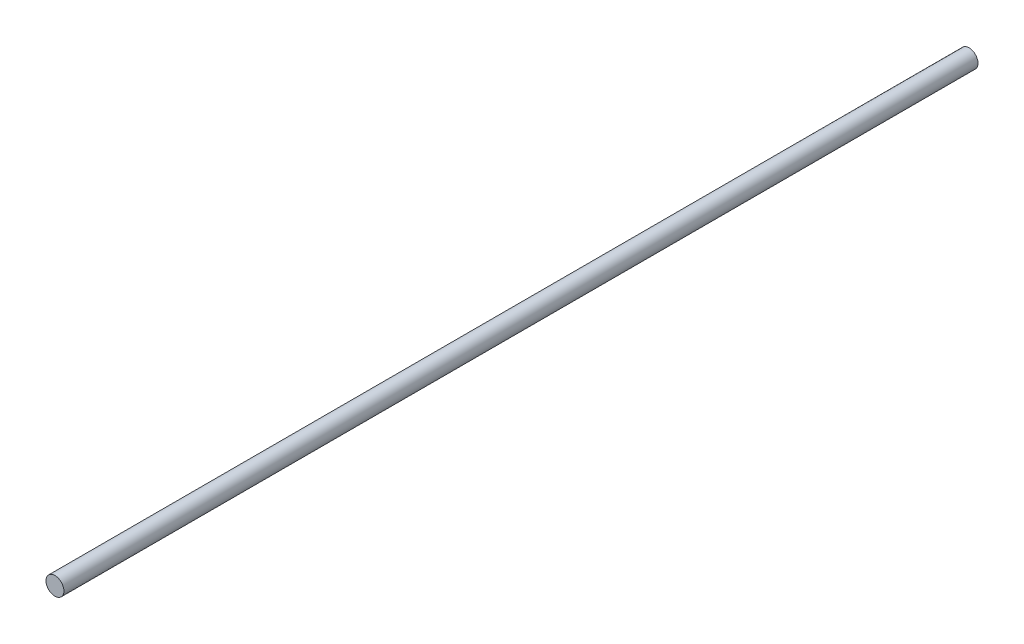
SolidWorks part; units mm, degrees
ref_plane "Front Plane" through (0, 0, 0) normal (0, 0, 1) x (1, 0, 0)
ref_plane "Top Plane" through (0, 0, 0) normal (0, 1, 0) x (1, 0, 0)
ref_plane "Right Plane" through (0, 0, 0) normal (1, 0, 0) x (0, 0, -1)
sketch "Sketch1" plane through (0, 0, 0) normal (0, 0, 1) x (1, 0, 0)
  circle A0 centre (0, 0) radius 5
  dimension "D1" = 10
extrude "Boss-Extrude1" add sketch "Sketch1" along normal blind 510
